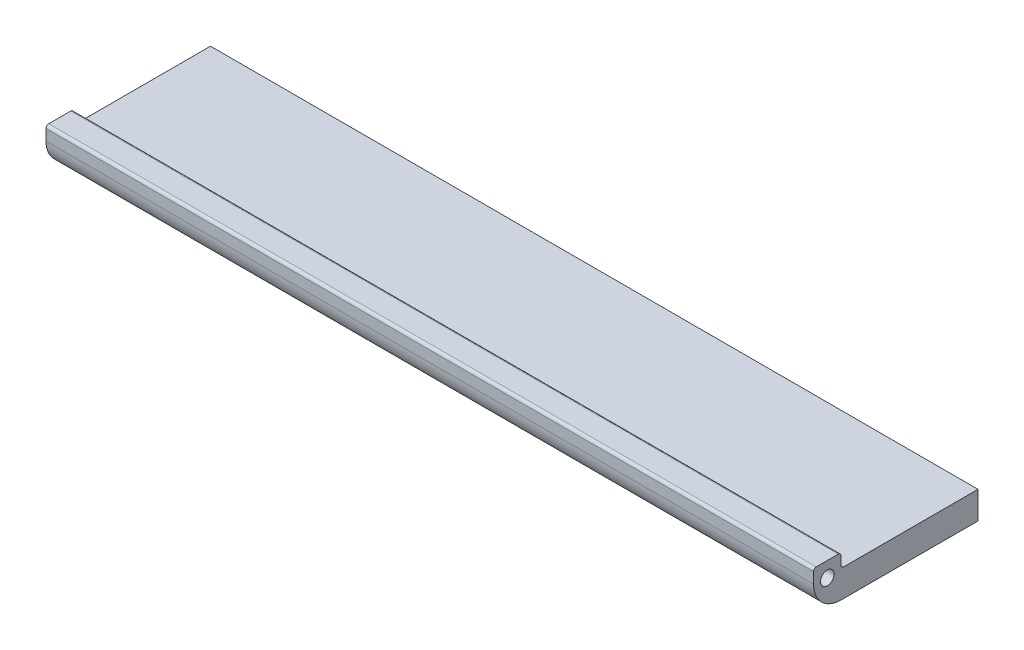
SolidWorks part; units mm, degrees
ref_plane "Front Plane" through (0, 0, 0) normal (0, 0, 1) x (1, 0, 0)
ref_plane "Top Plane" through (0, 0, 0) normal (0, 1, 0) x (1, 0, 0)
ref_plane "Right Plane" through (0, 0, 0) normal (1, 0, 0) x (0, 0, -1)
sketch "Sketch1" plane through (0, 0, 0) normal (0, 1, 0) x (1, 0, 0)
  line L1 (-140, 0) -> (140, 0)
  line L2 (-140, 0) -> (-140, -60)
  line L3 (-140, -60) -> (140, -60)
  line L4 (140, 0) -> (140, -60)
  dimension "D1" = 140
  dimension "D2" = 140
  dimension "D3" = 60
extrude "Boss-Extrude1" add sketch "Sketch1" along normal blind 10
sketch "Sketch2" plane through (0, 10, 0) normal (0, 1, 0) x (1, 0, 0)
  line L0 (140, -60) -> (140, 0) construction
  line L1 (-140, -60) -> (140, -60)
  line L2 (-140, -60) -> (-140, -50)
  line L3 (-140, -50) -> (140, -50)
  line L4 (140, -60) -> (140, -50)
  dimension "D1" = 10
extrude "Boss-Extrude2" add sketch "Sketch2" along normal blind 5
sketch "Sketch3" plane through (140, 0, 0) normal (1, 0, 0) x (0, 0, -1)
  line L0 (-60, 15) -> (-60, 0) construction
  line L2 (-60, 15) -> (-50, 15) construction
  circle A0 centre (-55, 9.5) radius 2.5
  point P6 (-54.793, 15)
  dimension "D1" = 5
  dimension "D2" = 5
  dimension "D3" = 5.5
extrude "Cut-Extrude1" cut sketch "Sketch3" against normal through all
fillet "Fillet1" radius 10 1 edges at (0, 0, 60)
fillet "Fillet2" radius 1 1 edges at (0, 15, 60)
fillet "Fillet3" radius 1 1 edges at (0, 15, 50)
fillet "Fillet4" radius 1 1 edges
